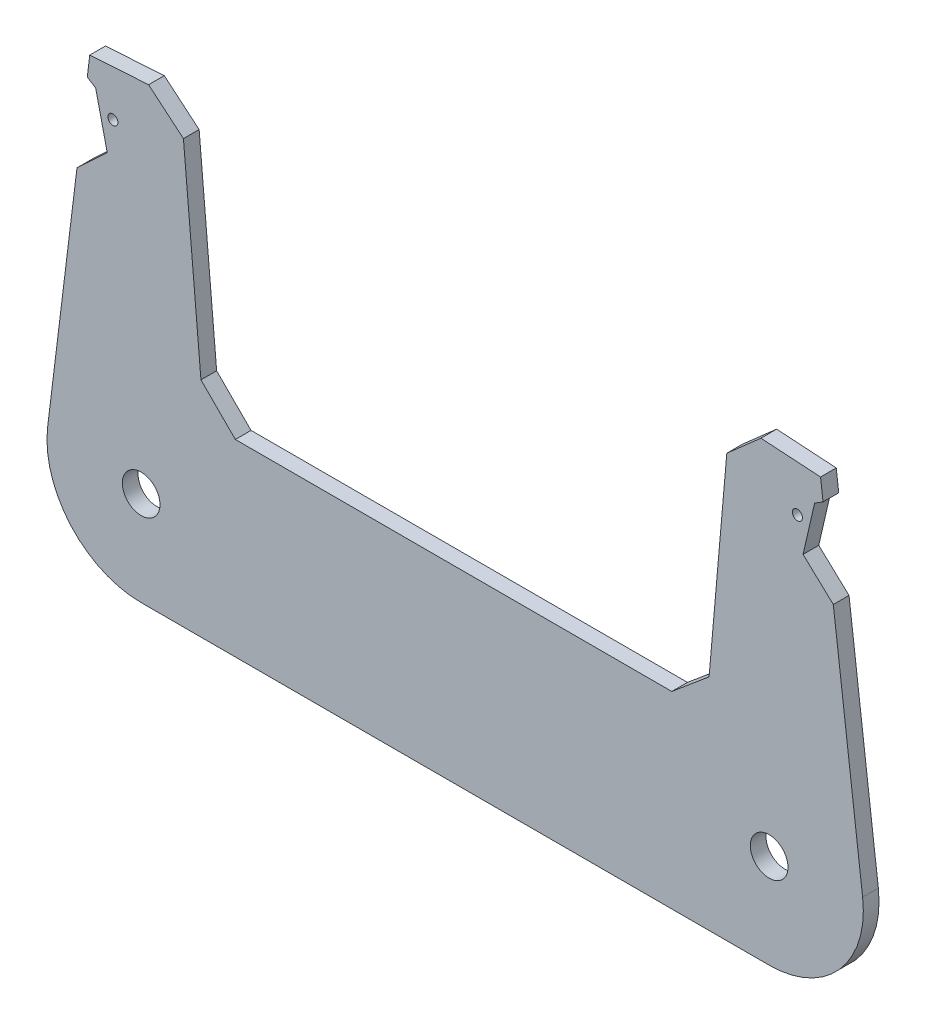
SolidWorks part; units mm, degrees
ref_plane "Front Plane" through (0, 0, 0) normal (0, 0, 1) x (1, 0, 0)
ref_plane "Top Plane" through (0, 0, 0) normal (0, 1, 0) x (1, 0, 0)
ref_plane "Right Plane" through (0, 0, 0) normal (1, 0, 0) x (0, 0, -1)
sketch "Sketch1" plane through (0, 0, 0) normal (0, 0, 1) x (1, 0, 0)
  line L1 (0, -30) -> (0, 90.9731) construction
  line L2 (100, 30) -> (-100, 30)
  line L3 (-100, -30) -> (100, -30)
  line L4 (80, 30) -> (-80, 30)
  line L5 (-100, -30) -> (100, -30)
  line L7 (-116.3708, 112.8362) -> (-87.4082, 114.6765)
  line L8 (-87.4082, 114.6765) -> (-80, 30)
  line L9 (-100, 30) -> (100, 30) construction
  line L14 (87.4082, 114.6765) -> (80, 30)
  line L15 (116.3708, 112.8362) -> (87.4082, 114.6765)
  line L16 (-116.3708, 112.8362) -> (-129.7764, 3.6561)
  line L21 (116.3708, 112.8362) -> (129.7764, 3.6561)
  circle A1 centre (-100, 0) radius 6
  arc A2 (100, -30) -> (100, 30) centre (100, 0) ccw
  arc A3 (-100, 30) -> (-100, -30) centre (-100, 0) ccw
  circle A6 centre (100, 0) radius 6
  arc A7 (100, -30) -> (129.7764, 3.6561) centre (100, 0) ccw
  arc A9 (-100, -30) -> (-129.7764, 3.6561) centre (-100, 0) cw
  dimension "D10" = 12
  dimension "D2" = 110
  dimension "D3" = 83
  dimension "D5" = 85
  dimension "D7" = 85
  dimension "D8" = 80
  dimension "D1" = 0
extrude "Boss-Extrude1" add sketch "Sketch1" along normal blind 5
sketch "Sketch2" plane through (0, 0, 0) normal (0, 0, -1) x (-1, 0, 0)
  line L0 (-80, 30) -> (80, 30) construction
  line L1 (0, -30) -> (0, 30) construction
  line L2 (120.4388, 79.7048) -> (110.7965, 88.6963)
  line L3 (116.3708, 112.8362) -> (129.7764, 3.6561) construction
  line L5 (114.4904, 104.6963) -> (117.165, 106.3676)
  line L6 (117.165, 106.3676) -> (120.4388, 79.7048)
  line L7 (-117.165, 106.3676) -> (-120.4388, 79.7048)
  line L8 (-114.4904, 104.6963) -> (-117.165, 106.3676)
  line L9 (-110.7965, 88.6963) -> (-114.4904, 104.6963)
  line L10 (-120.4388, 79.7048) -> (-110.7965, 88.6963)
  line L11 (114.4904, 104.6963) -> (110.7965, 88.6963)
  circle A0 centre (109, 98.6963) radius 1.6
  circle A1 centre (-109, 98.6963) radius 1.6
  dimension "D3" = 3.2
  dimension "D1" = 68.6963
  dimension "D2" = 29
  dimension "D4" = 4
  dimension "D5" = 20
  dimension "D6" = 45
  dimension "D7" = 10
  dimension "D8" = 6
  dimension "D9" = 60
extrude "Cut-Extrude1" cut sketch "Sketch2" against normal blind 25
chamfer "Chamfer1" distance 10 angle 45 2 edges at (-87.4082, 114.6765, 2.5) (87.4082, 114.6765, 2.5)
chamfer "Chamfer2" distance 10 angle 45 2 edges at (80, 30, 2.5) (-80, 30, 2.5)
